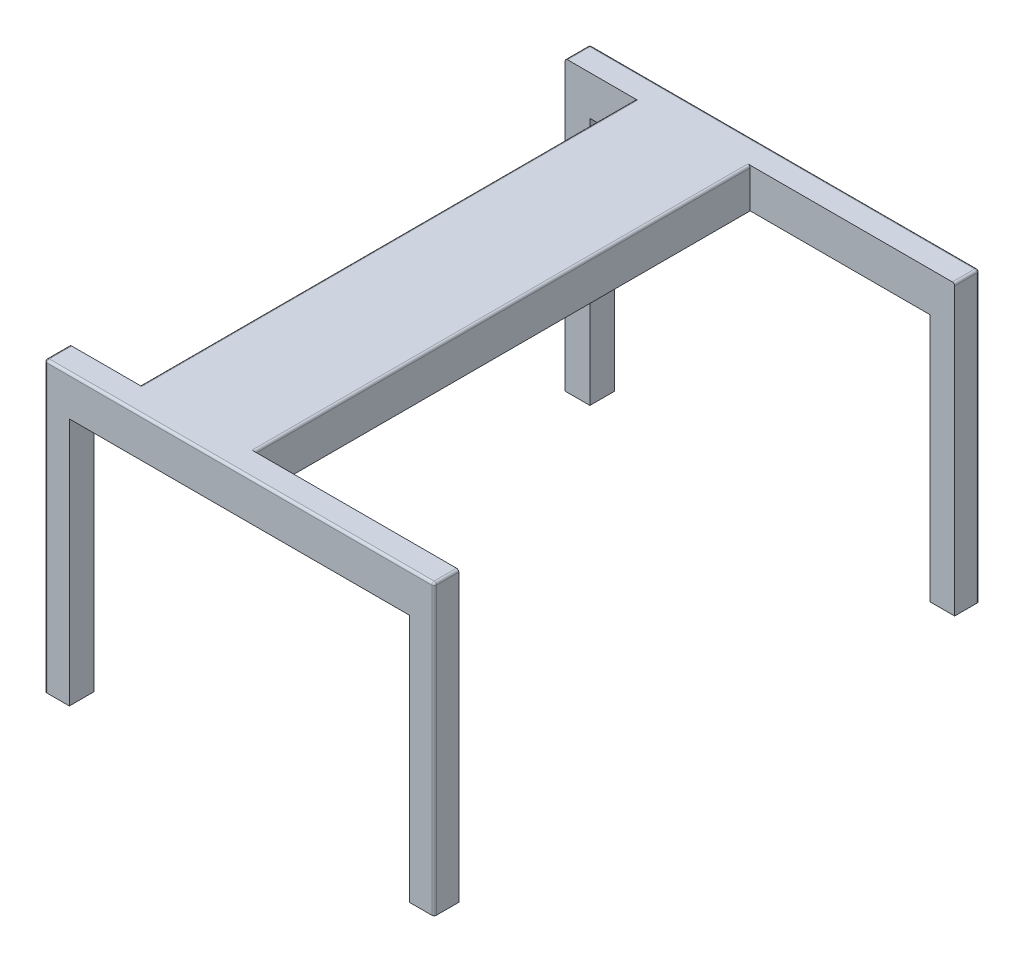
SolidWorks part; units mm, degrees
ref_plane "Alzado" through (0, 0, 0) normal (0, 0, 1) x (1, 0, 0)
ref_plane "Planta" through (0, 0, 0) normal (0, 1, 0) x (1, 0, 0)
ref_plane "Vista lateral" through (0, 0, 0) normal (1, 0, 0) x (0, 0, -1)
sketch "Croquis1" plane through (0, 0, 0) normal (0, 0, 1) x (1, 0, 0)
  line L1 (0, 0) -> (1000, 0)
  line L2 (0, 0) -> (0, -740)
  line L3 (0, -740) -> (1000, -740)
  line L4 (1000, 0) -> (1000, -740)
  dimension "D1" = 740
  dimension "D2" = 1000
extrude "Saliente-Extruir1" add sketch "Croquis1" along normal blind 1400
sketch "Croquis2" plane through (0, 0, 1400) normal (0, 0, 1) x (1, 0, 0)
  line L0 (0, -740) -> (1000, -740) construction
  line L1 (63.5, -740) -> (936.5, -740)
  line L2 (63.5, -740) -> (63.5, -101.6)
  line L3 (63.5, -101.6) -> (936.5, -101.6)
  line L4 (936.5, -740) -> (936.5, -101.6)
  line L5 (0, 0) -> (0, -740) construction
  line L6 (1000, -740) -> (1000, 0) construction
  line L7 (1000, 0) -> (0, 0) construction
  dimension "D1" = 63.5
  dimension "D2" = 63.5
  dimension "D3" = 101.6
extrude "Cortar-Extruir1" cut sketch "Croquis2" against normal up to surface (1400 mm away) up to face at (500, -370, 0)
sketch "Croquis3" plane through (1000, 0, 0) normal (1, 0, 0) x (0, 0, -1)
  line L0 (0, -101.6) -> (-1400, -101.6) construction
  line L1 (-1336.5, -101.6) -> (-63.5, -101.6)
  line L2 (-1336.5, -101.6) -> (-1336.5, -740)
  line L3 (-1336.5, -740) -> (-63.5, -740)
  line L4 (-63.5, -101.6) -> (-63.5, -740)
  line L5 (-1400, -740) -> (0, -740) construction
  line L6 (-1400, -740) -> (-1400, 0) construction
  line L7 (0, -740) -> (0, 0) construction
  dimension "D1" = 63.5
  dimension "D2" = 63.5
extrude "Cortar-Extruir2" cut sketch "Croquis3" against normal blind 1000
sketch "Croquis4" plane through (0, 0, 0) normal (0, 1, 0) x (1, 0, 0)
  line L0 (500, 0) -> (500, -1400) construction
  line L1 (0, -63.5) -> (180, -63.5)
  line L2 (0, -63.5) -> (0, -1336.5)
  line L3 (0, -1336.5) -> (180, -1336.5)
  line L4 (180, -63.5) -> (180, -1336.5)
  line L5 (1000, 0) -> (0, 0) construction
  line L6 (1000, -1400) -> (0, -1400) construction
  line L8 (1000, -63.5) -> (475, -63.5)
  line L9 (1000, -63.5) -> (1000, -1336.5)
  line L10 (1000, -1336.5) -> (475, -1336.5)
  line L11 (475, -63.5) -> (475, -1336.5)
  dimension "D1" = 180
  dimension "D2" = 525
  dimension "D3" = 63.5
  dimension "D4" = 63.5
  dimension "D5" = 63.5
extrude "Cortar-Extruir3" cut sketch "Croquis4" against normal blind 200
fillet "Redondeo1" radius 6 4 edges at (0, 0, 1368.25) (0, 0, 31.75) (1000, 0, 31.75) (1000, 0, 1368.25)
fillet "Redondeo2" radius 6 2 edges at (180, 0, 700) (475, 0, 700)
fillet "Redondeo4" radius 6 10 edges at (1000, -373, 0) (998.2426, -1.7574, 0) (0, -373, 0) (1.7574, -1.7574, 0) (1000, -373, 1400) (998.2426, -1.7574, 1400) (0, -373, 1400) (1.7574, -1.7574, 1400) (500, 0, 0) (500, 0, 1400)
